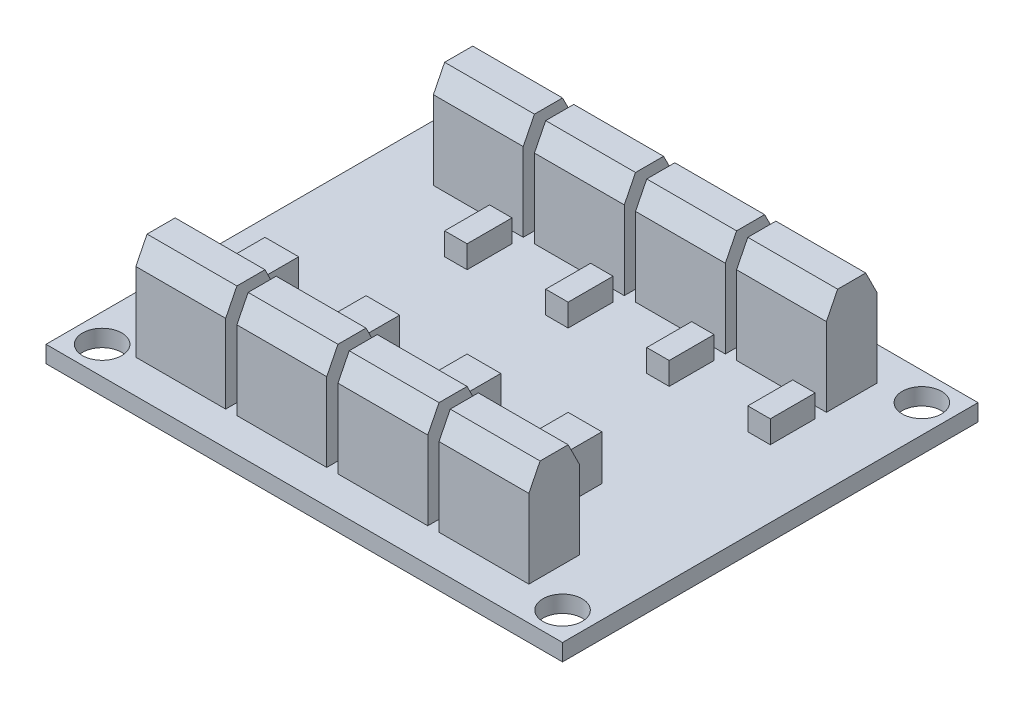
SolidWorks part; units mm, degrees
ref_plane "Front Plane" through (0, 0, 0) normal (0, 0, 1) x (1, 0, 0)
ref_plane "Top Plane" through (0, 0, 0) normal (0, 1, 0) x (1, 0, 0)
ref_plane "Right Plane" through (0, 0, 0) normal (1, 0, 0) x (0, 0, -1)
sketch "Sketch1" plane through (0, 0, 0) normal (0, 1, 0) x (1, 0, 0)
  line L0 (13.9332, 0) -> (0, 0) construction
  line L1 (-23, -18.5) -> (23, -18.5)
  line L2 (-23, -18.5) -> (-23, 18.5)
  line L3 (-23, 18.5) -> (23, 18.5)
  line L4 (23, -18.5) -> (23, 18.5)
  line L5 (-23, -18.5) -> (23, 18.5) construction
  line L6 (-23, 18.5) -> (23, -18.5) construction
  line L7 (0, 0) -> (0, 12.3917) construction
  circle A0 centre (20.5, 16) radius 1.75
  circle A1 centre (20.5, -16) radius 1.75
  circle A2 centre (-20.5, -16) radius 1.75
  circle A3 centre (-20.5, 16) radius 1.75
  point P0 (0, 0)
  dimension "D3" = 3.5
  dimension "D1" = 37
  dimension "D2" = 46
  dimension "D4" = 2.5
  dimension "D5" = 2.5
extrude "Boss-Extrude1" add sketch "Sketch1" along normal mid plane 1.5
sketch "Sketch2" plane through (0, 0.75, 0) normal (0, 1, 0) x (1, 0, 0)
  line L0 (23, 18.5) -> (-23, 18.5) construction
  line L1 (9, 15.5) -> (17, 15.5)
  line L2 (9, 15.5) -> (9, 11)
  line L3 (9, 11) -> (17, 11)
  line L4 (17, 15.5) -> (17, 11)
  line L5 (23, -18.5) -> (23, 18.5) construction
  line L6 (0, 15.5) -> (8, 15.5)
  line L7 (0, 15.5) -> (0, 11)
  line L8 (0, 11) -> (8, 11)
  line L9 (8, 15.5) -> (8, 11)
  line L10 (-9, 15.5) -> (-1, 15.5)
  line L11 (-9, 15.5) -> (-9, 11)
  line L12 (-9, 11) -> (-1, 11)
  line L13 (-1, 15.5) -> (-1, 11)
  line L14 (-18, 15.5) -> (-10, 15.5)
  line L15 (-18, 15.5) -> (-18, 11)
  line L16 (-18, 11) -> (-10, 11)
  line L17 (-10, 15.5) -> (-10, 11)
  line L34 (-23, 0) -> (0, 0) construction
  line L35 (-23, 18.5) -> (-23, -18.5) construction
  line L52 (-10, -15.5) -> (-10, -11)
  line L53 (-18, -11) -> (-10, -11)
  line L54 (-18, -15.5) -> (-18, -11)
  line L55 (-18, -15.5) -> (-10, -15.5)
  line L56 (-1, -15.5) -> (-1, -11)
  line L57 (-9, -11) -> (-1, -11)
  line L58 (-9, -15.5) -> (-9, -11)
  line L59 (-9, -15.5) -> (-1, -15.5)
  line L60 (8, -15.5) -> (8, -11)
  line L61 (0, -11) -> (8, -11)
  line L62 (0, -15.5) -> (0, -11)
  line L63 (0, -15.5) -> (8, -15.5)
  line L64 (17, -15.5) -> (17, -11)
  line L65 (9, -11) -> (17, -11)
  line L66 (9, -15.5) -> (9, -11)
  line L67 (9, -15.5) -> (17, -15.5)
  line L68 (-27, 15.5) -> (-19, 15.5) [skipped]
  line L69 (-27, 15.5) -> (-27, 11) [skipped]
  line L70 (-27, 11) -> (-19, 11) [skipped]
  line L71 (-19, 15.5) -> (-19, 11) [skipped]
  line L72 (-36, 15.5) -> (-28, 15.5) [skipped]
  line L73 (-36, 15.5) -> (-36, 11) [skipped]
  line L74 (-36, 11) -> (-28, 11) [skipped]
  line L75 (-28, 15.5) -> (-28, 11) [skipped]
  line L76 (-45, 15.5) -> (-37, 15.5) [skipped]
  line L77 (-45, 15.5) -> (-45, 11) [skipped]
  line L78 (-45, 11) -> (-37, 11) [skipped]
  line L79 (-37, 15.5) -> (-37, 11) [skipped]
  line L80 (-54, 15.5) -> (-46, 15.5) [skipped]
  line L81 (-54, 15.5) -> (-54, 11) [skipped]
  line L82 (-54, 11) -> (-46, 11) [skipped]
  line L83 (-46, 15.5) -> (-46, 11) [skipped]
  dimension "D1" = 8
  dimension "D2" = 4.5
  dimension "D3" = 3
  dimension "D4" = 6
  dimension "D5" = 8
extrude "Boss-Extrude2" add sketch "Sketch2" along normal blind 9
sketch "Sketch3" plane through (17, 0, 0) normal (1, 0, 0) x (0, 0, -1)
  line L0 (-15.5, 7.75) -> (-14.5, 9.75)
  line L1 (-15.5, 9.75) -> (-15.5, 0.75) construction
  line L2 (-15.5, 9.75) -> (-11, 9.75) construction
  line L3 (-14.5, 9.75) -> (-15.5, 9.75)
  line L4 (-15.5, 9.75) -> (-15.5, 7.75)
  line L5 (-13.25, 9.75) -> (-13.25, 7.176) construction
  line L6 (-11, 9.75) -> (-11, 7.75)
  line L7 (-12, 9.75) -> (-11, 9.75)
  line L8 (-11, 7.75) -> (-12, 9.75)
  line L9 (0, 14.3027) -> (0, 0) construction
  line L10 (-15.5, 7.75) -> (-14.5, 9.75)
  line L11 (-14.5, 9.75) -> (-15.5, 9.75)
  line L12 (-15.5, 9.75) -> (-15.5, 7.75)
  line L13 (-11, 9.75) -> (-11, 7.75)
  line L14 (-12, 9.75) -> (-11, 9.75)
  line L15 (-11, 7.75) -> (-12, 9.75)
  line L16 (13.25, 9.75) -> (13.25, 7.176) construction
  line L17 (11, 7.75) -> (12, 9.75)
  line L18 (12, 9.75) -> (11, 9.75)
  line L19 (11, 9.75) -> (11, 7.75)
  line L20 (15.5, 9.75) -> (15.5, 7.75)
  line L21 (14.5, 9.75) -> (15.5, 9.75)
  line L22 (15.5, 7.75) -> (14.5, 9.75)
  line L23 (11, 7.75) -> (12, 9.75)
  line L24 (12, 9.75) -> (11, 9.75)
  line L25 (11, 9.75) -> (11, 7.75)
  line L26 (15.5, 9.75) -> (15.5, 7.75)
  line L27 (14.5, 9.75) -> (15.5, 9.75)
  line L28 (15.5, 7.75) -> (14.5, 9.75)
  line M6 (-11, 0.75) -> (-11, 9.75)
  line M7 (-11, 9.75) -> (-15.5, 9.75)
  line M8 (-15.5, 9.75) -> (-15.5, 0.75)
  dimension "D1" = 1
  dimension "D2" = 2
extrude "Cut-Extrude2" cut sketch "Sketch3" against normal blind 124 contours L0 M8 M7 | L8 M6 M7 | L18 L19 L17 | L22 L20 L21
sketch "Sketch4" plane through (0, 0.75, 0) normal (0, 1, 0) x (1, 0, 0)
  line L0 (17, 11) -> (17, 12) construction
  line L1 (17, 10) -> (15, 10)
  line L2 (17, 10) -> (17, 6)
  line L3 (17, 6) -> (15, 6)
  line L4 (15, 10) -> (15, 6)
  line L5 (9, 11) -> (17, 11) construction
  line L6 (8, 10) -> (6, 10)
  line L7 (8, 10) -> (8, 6)
  line L8 (8, 6) -> (6, 6)
  line L9 (6, 10) -> (6, 6)
  line L10 (-1, 10) -> (-3, 10)
  line L11 (-1, 10) -> (-1, 6)
  line L12 (-1, 6) -> (-3, 6)
  line L13 (-3, 10) -> (-3, 6)
  line L14 (-10, 10) -> (-12, 10)
  line L15 (-10, 10) -> (-10, 6)
  line L16 (-10, 6) -> (-12, 6)
  line L17 (-12, 10) -> (-12, 6)
  line L34 (-28, 10) -> (-30, 10) [skipped]
  line L35 (-28, 10) -> (-28, 6) [skipped]
  line L36 (-28, 6) -> (-30, 6) [skipped]
  line L37 (-30, 10) -> (-30, 6) [skipped]
  line L38 (-37, 10) -> (-39, 10) [skipped]
  line L39 (-37, 10) -> (-37, 6) [skipped]
  line L40 (-37, 6) -> (-39, 6) [skipped]
  line L41 (-39, 10) -> (-39, 6) [skipped]
  line L42 (-46, 10) -> (-48, 10) [skipped]
  line L43 (-46, 10) -> (-46, 6) [skipped]
  line L44 (-46, 6) -> (-48, 6) [skipped]
  line L45 (-48, 10) -> (-48, 6) [skipped]
  line L46 (-19, 10) -> (-21, 10) [skipped]
  line L47 (-19, 10) -> (-19, 6) [skipped]
  line L48 (-19, 6) -> (-21, 6) [skipped]
  line L49 (-21, 10) -> (-21, 6) [skipped]
  point P4 (17, 8)
  dimension "D1" = 0
  dimension "D2" = 4
  dimension "D3" = 2
  dimension "D4" = 1
  dimension "D5" = 8
extrude "Boss-Extrude3" add sketch "Sketch4" along normal blind 2
sketch "Sketch5" plane through (0, 0.75, 0) normal (0, 1, 0) x (1, 0, 0)
  line L10 (-17.5, -9.5) -> (-14.5, -9.5)
  line L11 (-17.5, -9.5) -> (-17.5, -4.5)
  line L12 (-17.5, -4.5) -> (-14.5, -4.5)
  line L13 (-14.5, -9.5) -> (-14.5, -4.5)
  line L14 (-8.5, -9.5) -> (-5.5, -9.5)
  line L15 (-8.5, -9.5) -> (-8.5, -4.5)
  line L16 (-8.5, -4.5) -> (-5.5, -4.5)
  line L17 (-5.5, -9.5) -> (-5.5, -4.5)
  line L18 (0.5, -9.5) -> (3.5, -9.5)
  line L19 (0.5, -9.5) -> (0.5, -4.5)
  line L20 (0.5, -4.5) -> (3.5, -4.5)
  line L21 (3.5, -9.5) -> (3.5, -4.5)
  line L22 (9.5, -9.5) -> (12.5, -9.5)
  line L23 (9.5, -9.5) -> (9.5, -4.5)
  line L24 (9.5, -4.5) -> (12.5, -4.5)
  line L25 (12.5, -9.5) -> (12.5, -4.5)
extrude "Boss-Extrude4" add sketch "Sketch5" along normal blind 4
